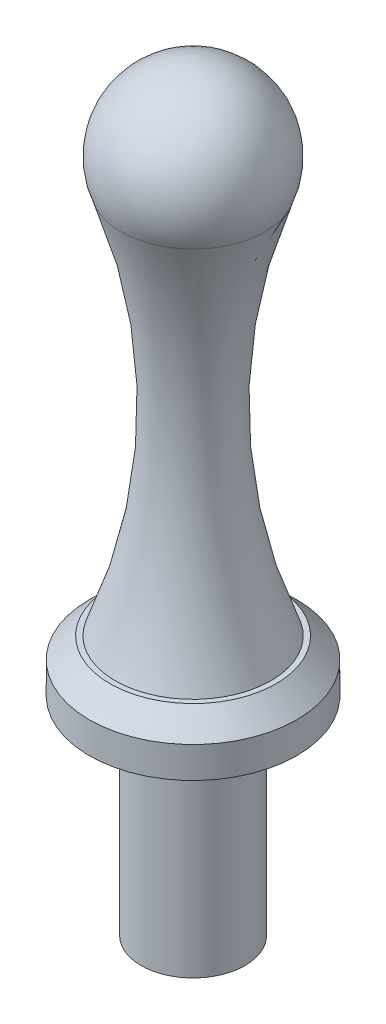
SolidWorks part; units mm, degrees
material "Chrome Stainless Steel"
ref_plane "Front Plane" through (0, 0, 0) normal (0, 0, 1) x (1, 0, 0)
ref_plane "Top Plane" through (0, 0, 0) normal (0, 1, 0) x (1, 0, 0)
ref_plane "Right Plane" through (0, 0, 0) normal (1, 0, 0) x (0, 0, -1)
sketch "Sketch1" plane through (0, 0, 0) normal (0, 0, 1) x (1, 0, 0)
  line L0 (0, 6.35) -> (0, 34.925) construction
  line L1 (-3.175, -6.35) -> (3.175, -6.35)
  line L2 (-3.175, -6.35) -> (-3.175, 6.35)
  line L3 (-3.175, 6.35) -> (3.175, 6.35)
  line L4 (3.175, -6.35) -> (3.175, 6.35)
  line L5 (-3.175, -6.35) -> (3.175, 6.35) construction
  line L6 (-3.175, 6.35) -> (3.175, -6.35) construction
  line L7 (-4.7625, 34.925) -> (-4.7625, 9.525) construction
  line L8 (-6.35, 9.525) -> (6.35, 9.525)
  line L9 (-6.35, 9.525) -> (-6.35, 6.35)
  line L10 (-6.35, 6.35) -> (6.35, 6.35)
  line L11 (6.35, 9.525) -> (6.35, 6.35)
  line L12 (-6.35, 9.525) -> (6.35, 6.35) construction
  line L13 (-6.35, 6.35) -> (6.35, 9.525) construction
  line L14 (-4.7625, 34.925) -> (0, 30.1625) construction
  line L15 (-2.3812, 32.5437) -> (-3.3676, 31.5574) construction
  line L16 (0, 30.1625) -> (0, -6.35)
  line L17 (0, 39.6875) -> (0, 30.1625)
  line L18 (0, 45.9243) -> (0, 52.688) construction
  circle A0 centre (0, 34.925) radius 4.7625
  arc A1 (-4.7625, 34.925) -> (-3.3676, 31.5574) centre (0, 34.925) ccw
  arc A2 (-4.4, 33.1025) -> (-4.7625, 9.525) centre (-35.5173, 21.7894) cw
  point P0 (0, 0)
  point P9 (0, 7.9375)
  dimension "D3" = 9.525
  dimension "D1" = 6.35
  dimension "D2" = 12.7
  dimension "D4" = 28.575
  dimension "D5" = 3.175
  dimension "D6" = 12.7
revolve "Revolve1" add sketch "Sketch1" angle 360 about L18
chamfer "Chamfer1" distance 1.27 angle 45 1 edges at (6.35, 9.525, 0)
